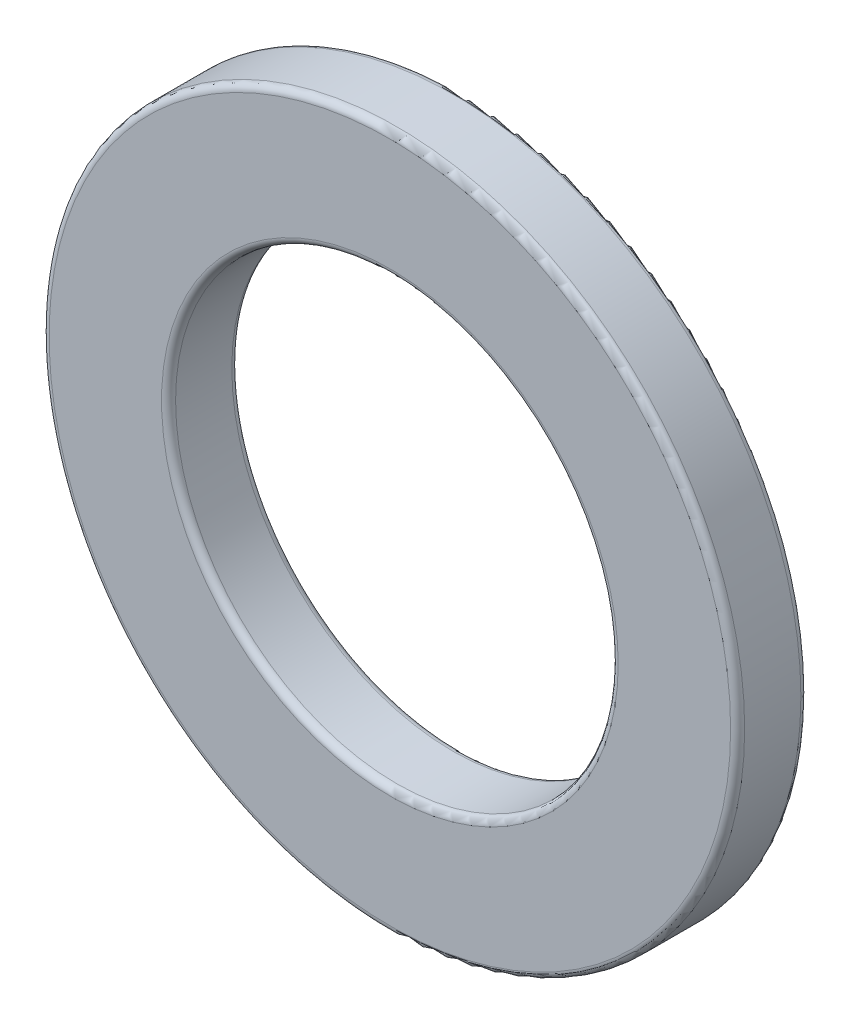
SolidWorks part; units mm, degrees
material "Plain Carbon Steel"
ref_plane "Front Plane" through (0, 0, 0) normal (0, 0, 1) x (1, 0, 0)
ref_plane "Top Plane" through (0, 0, 0) normal (0, 1, 0) x (1, 0, 0)
ref_plane "Right Plane" through (0, 0, 0) normal (1, 0, 0) x (0, 0, -1)
sketch "Sketch2" plane through (0, 0, 0) normal (0, 0, 1) x (1, 0, 0)
  circle A0 centre (0, 0) radius 1.575
  circle A1 centre (0, 0) radius 2.475
  dimension "D1" = 3.15
  dimension "D2" = 4.95
extrude "Boss-Extrude1" add sketch "Sketch2" along normal blind 0.5
fillet "Fillet2" radius 0.05 4 edges at (1.575, 0, 0) (2.475, 0, 0) (1.575, 0, 0.5) (2.475, 0, 0.5)
